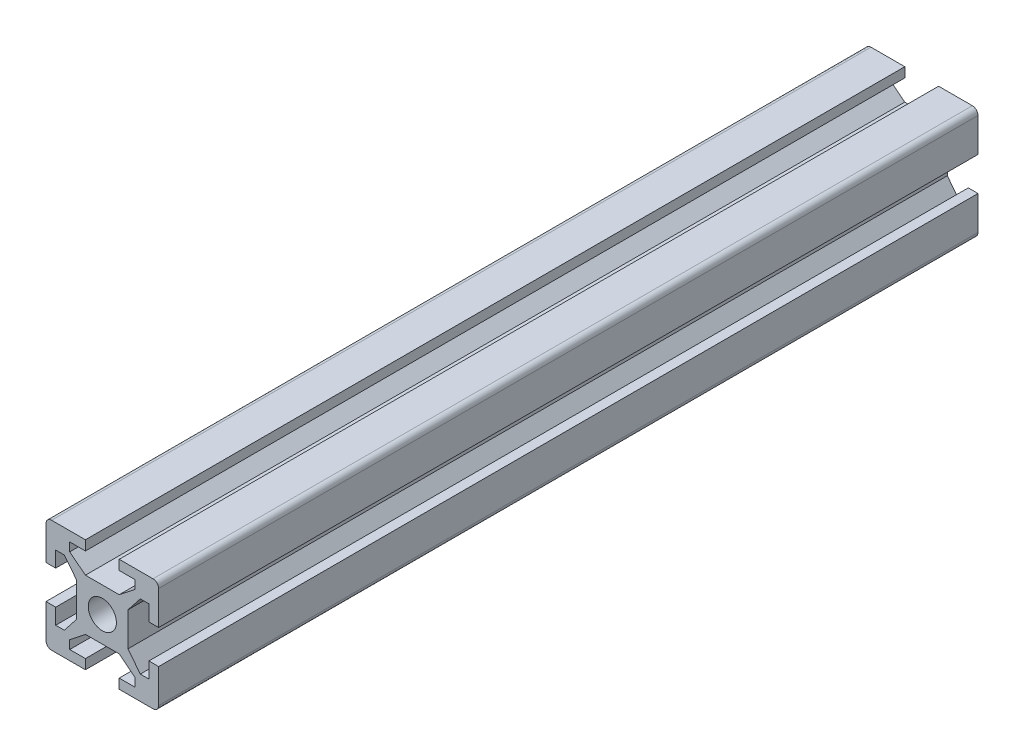
SolidWorks part; units mm, degrees
ref_plane "Front Plane" through (0, 0, 0) normal (0, 0, 1) x (1, 0, 0)
ref_plane "Top Plane" through (0, 0, 0) normal (0, 1, 0) x (1, 0, 0)
ref_plane "Right Plane" through (0, 0, 0) normal (1, 0, 0) x (0, 0, -1)
sketch "Sketch1" plane through (0, 0, 0) normal (0, 0, 1) x (1, 0, 0)
  line L18 (0, 0) -> (0, 20.5117) construction
  line L39 (-10, 10) -> (-3, 10)
  line L41 (10, 10) -> (3, 10)
  line L43 (-10, 10) -> (-10, 3)
  line L45 (-10, -10) -> (-10, -3)
  line L47 (-10, -10) -> (-3, -10)
  line L49 (3, -10) -> (10, -10)
  line L51 (10, -10) -> (10, -3)
  line L53 (10, 3) -> (10, 10)
  line L55 (-3, 10) -> (-3, 8.2726)
  line L56 (-3, 8.2726) -> (-5.7838, 8.2726)
  line L57 (-5.7838, 8.2726) -> (-5.7838, 6.748)
  line L58 (-5.7838, 6.748) -> (-3, 4.5508)
  line L59 (-3, 4.5508) -> (3, 4.5508)
  line L60 (3, 10) -> (3, 8.2726)
  line L61 (3, 8.2726) -> (5.7838, 8.2726)
  line L62 (5.7838, 8.2726) -> (5.7838, 6.748)
  line L63 (5.7838, 6.748) -> (3, 4.5508)
  line L64 (10, 3) -> (8.2726, 3)
  line L65 (8.2726, 3) -> (8.2726, 5.7838)
  line L66 (8.2726, 5.7838) -> (6.748, 5.7838)
  line L67 (10, -3) -> (8.2726, -3)
  line L68 (8.2726, -3) -> (8.2726, -5.7838)
  line L69 (8.2726, -5.7838) -> (6.748, -5.7838)
  line L70 (4.55, -2.9994) -> (4.55, 3.0006)
  line L71 (4.55, -2.9994) -> (6.748, -5.7838)
  line L72 (4.55, 3.0006) -> (6.748, 5.7838)
  line L73 (3, -10) -> (3, -8.2726)
  line L74 (3, -8.2726) -> (5.7838, -8.2726)
  line L75 (5.7838, -8.2726) -> (5.7838, -6.748)
  line L76 (-3, -10) -> (-3, -8.2726)
  line L77 (-3, -8.2726) -> (-5.7838, -8.2726)
  line L78 (-5.7838, -8.2726) -> (-5.7838, -6.748)
  line L79 (2.9994, -4.55) -> (-3.0006, -4.55)
  line L80 (5.7838, -6.748) -> (2.9994, -4.55)
  line L81 (-5.7838, -6.748) -> (-3.0006, -4.55)
  line L82 (-10, -3) -> (-8.2726, -3)
  line L83 (-8.2726, -3) -> (-8.2726, -5.7838)
  line L84 (-8.2726, -5.7838) -> (-6.748, -5.7838)
  line L85 (-10, 3) -> (-8.2726, 3)
  line L86 (-8.2726, 3) -> (-8.2726, 5.7838)
  line L87 (-8.2726, 5.7838) -> (-6.748, 5.7838)
  line L88 (-4.55, -3.0006) -> (-4.55, 2.9994)
  line L89 (-6.748, -5.7838) -> (-4.55, -3.0006)
  line L90 (-4.55, 2.9994) -> (-6.748, 5.7838)
  dimension "D9" = 7
  dimension "D17" = 2.7838
  dimension "D1" = 20
  dimension "D2" = 20
  dimension "D3" = 10
  dimension "D4" = 10
  dimension "D5" = 7
  dimension "D6" = 7
  dimension "D7" = 7
  dimension "D8" = 7
  dimension "D10" = 7
  dimension "D11" = 7
  dimension "D12" = 7
  dimension "D13" = 6
  dimension "D14" = 3
  dimension "D15" = 3.5464
  dimension "D16" = 1.5246
  dimension "D18" = 1.7274
  dimension "D19" = 4.55
  dimension "D20" = 4.55
  dimension "D21" = 4.55
  dimension "D22" = 10
  dimension "D23" = 10
  dimension "D24" = 10
  dimension "D25" = 10
  dimension "D26" = 10
  dimension "D27" = 10
  dimension "D28" = 6
  dimension "D29" = 6
  dimension "D30" = 6
  dimension "D31" = 6
extrude "Boss-Extrude1" add sketch "Sketch1" along normal mid plane 145.5
sketch "Sketch2" plane through (0, 0, 72.75) normal (0, 0, 1) x (1, 0, 0)
  circle A0 centre (0, 0) radius 2.5
  dimension "D1" = 5
extrude "Cut-Extrude1" cut sketch "Sketch2" against normal through all both and the other way through all
fillet "Fillet1" radius 1 4 edges at (-10, -10, 0) (10, -10, 0) (10, 10, 0) (-10, 10, 0)
